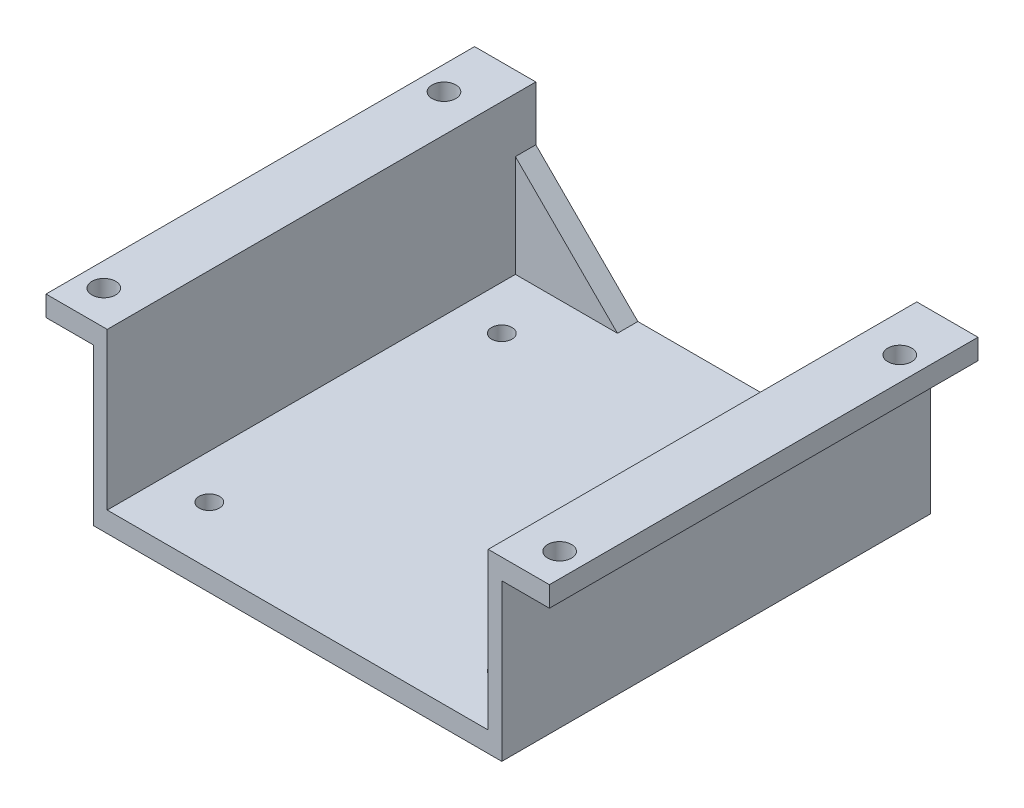
SolidWorks part; units mm, degrees
ref_plane "前视基准面" through (0, 0, 0) normal (0, 0, 1) x (1, 0, 0)
ref_plane "上视基准面" through (0, 0, 0) normal (0, 1, 0) x (1, 0, 0)
ref_plane "右视基准面" through (0, 0, 0) normal (1, 0, 0) x (0, 0, -1)
sketch "草图1" plane through (0, 0, 0) normal (0, 1, 0) x (1, 0, 0)
  line L1 (-30, -30) -> (30, -30)
  line L2 (-30, -30) -> (-30, 30)
  line L3 (-30, 30) -> (30, 30)
  line L4 (30, -30) -> (30, 30)
  line L5 (-30, -30) -> (30, 30) construction
  line L6 (-30, 30) -> (30, -30) construction
  point P0 (0, 0)
  dimension "D1" = 60
  dimension "D2" = 60
extrude "凸台-拉伸1" add sketch "草图1" along normal blind 3
sketch "草图2" plane through (0, 3, 0) normal (0, 1, 0) x (1, 0, 0)
  line L1 (-21.5, -21.5) -> (21.5, -21.5)
  line L2 (-21.5, -21.5) -> (-21.5, 21.5)
  line L3 (-21.5, 21.5) -> (21.5, 21.5)
  line L4 (21.5, -21.5) -> (21.5, 21.5)
  line L5 (-21.5, -21.5) -> (21.5, 21.5) construction
  line L6 (-21.5, 21.5) -> (21.5, -21.5) construction
  point P0 (0, 0)
  dimension "D1" = 43
  dimension "D2" = 43
sketch "草图3" plane through (0, 3, 0) normal (0, 1, 0) x (1, 0, 0)
  point P0 (-21.5, 21.5)
  point P3 (21.5, 21.5)
  point P6 (-21.5, -21.5)
  point P9 (21.5, -21.5)
hole_wizard "孔1" positions "草图3" profile "草图4" legacy end condition up to next
sketch "草图4" plane through (-21.5, 3, -21.5) normal (1, 0, 0) x (0, 0, 1)
  line L0 (0, 0) -> (0, 3)
  line L1 (0, 3) -> (1.5, 3)
  line L2 (1.5, 3) -> (1.5, 0)
  line L3 (1.5, 0) -> (0, 0)
  line L4 (0, 110) -> (0, -10) construction
  dimension "直径" = 3
  dimension "深度" = 3
sketch "草图5" plane through (0, 3, 0) normal (0, 1, 0) x (1, 0, 0)
  line L0 (-30, -30) -> (30, -30) construction
  line L1 (30, 30) -> (28, 30)
  line L2 (30, 30) -> (30, -30)
  line L3 (30, -30) -> (28, -30)
  line L4 (28, 30) -> (28, -30)
  line L6 (-30, 30) -> (-28, 30)
  line L7 (-30, 30) -> (-30, -30)
  line L8 (-30, -30) -> (-28, -30)
  line L9 (-28, 30) -> (-28, -30)
  dimension "D1" = 2
  dimension "D2" = 2
extrude "凸台-拉伸2" add sketch "草图5" along normal blind 23
sketch "草图6" plane through (30, 0, 0) normal (1, 0, 0) x (0, 0, -1)
  line L0 (30, 26) -> (30, 0) construction
  line L1 (-30, 26) -> (30, 26)
  line L2 (-30, 26) -> (-30, 23)
  line L3 (-30, 23) -> (30, 23)
  line L4 (30, 26) -> (30, 23)
  dimension "D1" = 3
extrude "凸台-拉伸3" add sketch "草图6" along normal blind 7
sketch "草图7" plane through (0, 26, 0) normal (0, 1, 0) x (1, 0, 0)
  line L0 (33.5, -30) -> (33.5, -25)
  line L1 (37, 30) -> (30, 30)
  line L2 (37, 30) -> (37, -30)
  line L3 (37, -30) -> (30, -30)
  line L4 (30, 30) -> (30, -30)
  line L5 (33.5, 30) -> (33.5, 25)
  dimension "D1" = 7
  dimension "D2" = 60
  dimension "D3" = 5
  dimension "D4" = 5
sketch "草图8" plane through (0, 26, 0) normal (0, 1, 0) x (1, 0, 0)
  point P0 (33.5, 25)
  point P3 (33.5, -25)
hole_wizard "孔2" positions "草图8" profile "草图9" legacy end condition through all
sketch "草图9" plane through (33.5, 26, -25) normal (1, 0, 0) x (0, 0, 1)
  line L0 (0, 0) -> (0, 26)
  line L1 (0, 26) -> (1.75, 26)
  line L2 (1.75, 26) -> (1.75, 0)
  line L3 (1.75, 0) -> (0, 0)
  line L4 (0, 110) -> (0, -10) construction
  dimension "直径" = 3.5
  dimension "深度" = 26
ref_plane "基准面1" through (0, 0, 0) normal (-1, 0, 0) x (0, 0, 1)
mirror "镜向1" about plane through (0, 0, 0) normal (-1, 0, 0) of "凸台-拉伸3", "孔2"
sketch "草图10" plane through (0, 0, 30) normal (0, 0, 1) x (1, 0, 0)
  line L0 (-28, 26) -> (-28, 3) construction
  line L1 (-37, 26) -> (-28, 26)
  line L2 (-37, 26) -> (-37, 23)
  line L3 (-37, 23) -> (-28, 23)
  line L4 (-28, 26) -> (-28, 23)
  line L6 (28, 26) -> (37, 26)
  line L7 (28, 26) -> (28, 23)
  line L8 (28, 23) -> (37, 23)
  line L9 (37, 26) -> (37, 23)
  dimension "D1" = 3
sketch "草图11" plane through (0, 0, -30) normal (0, 0, -1) x (-1, 0, 0)
  line L0 (-37, 26) -> (-28, 26)
  line L1 (-28, 26) -> (-28, 3)
  line L2 (-28, 3) -> (28, 3)
  line L3 (28, 3) -> (28, 26)
  line L4 (28, 26) -> (37, 26)
  line L5 (37, 26) -> (37, 23)
  line L6 (37, 23) -> (30, 23)
  line L7 (30, 23) -> (30, 0)
  line L8 (30, 0) -> (-30, 0)
  line L9 (-30, 0) -> (-30, 23)
  line L10 (-30, 23) -> (-37, 23)
  line L11 (-37, 23) -> (-37, 26)
extrude "凸台-拉伸4" add sketch "草图11" along normal blind 3
sketch "草图12" plane through (0, 0, -33) normal (0, 0, -1) x (-1, 0, 0)
  line L0 (-28, 18) -> (-13, 3)
  line L1 (-28, 3) -> (-28, 26) construction
  line L2 (21.5, 3) -> (-21.5, 3) construction
  line L3 (-13, 3) -> (-28, 3)
  line L4 (-28, 3) -> (-28, 18)
  line L5 (28, 18) -> (13, 3)
  line L6 (28, 26) -> (28, 3) construction
  line L7 (21.5, 3) -> (-21.5, 3) construction
  line L8 (13, 3) -> (28, 3)
  line L9 (28, 3) -> (28, 18)
  dimension "D1" = 15
  dimension "D2" = 45
  dimension "D3" = 15
  dimension "D4" = 45
extrude "凸台-拉伸5" add sketch "草图12" against normal blind 3
